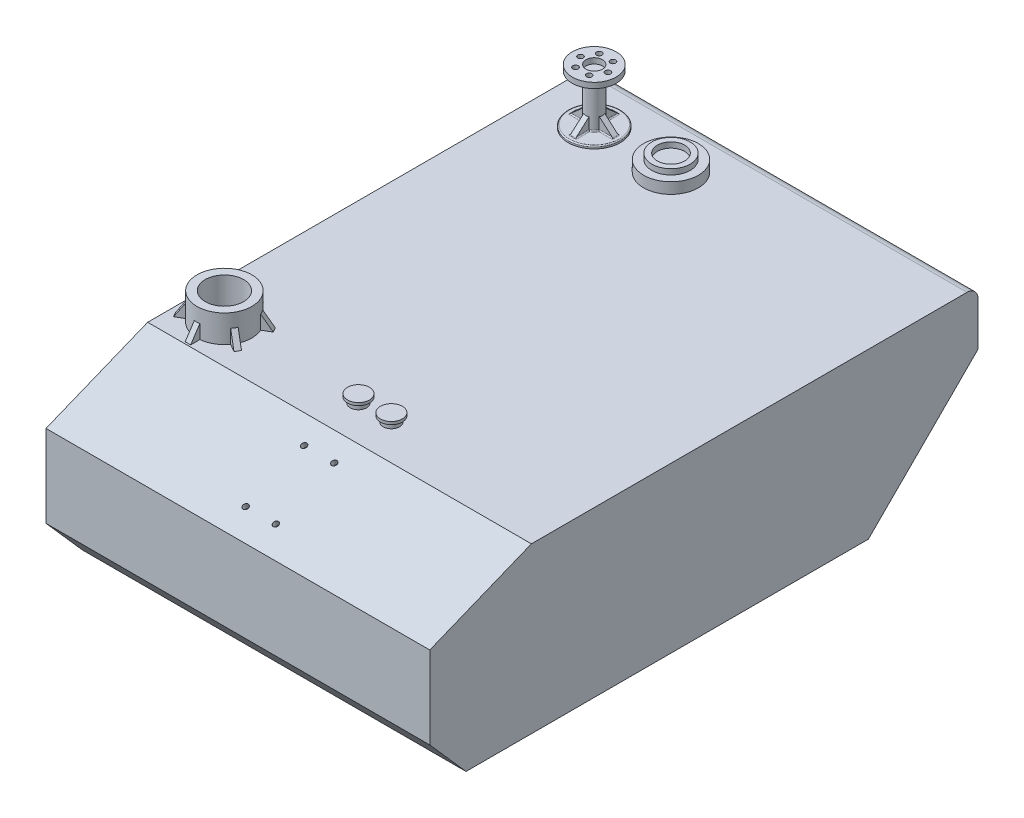
SolidWorks part; units mm, degrees
ref_plane "Front Plane" through (0, 0, 0) normal (0, 0, 1) x (1, 0, 0)
ref_plane "Top Plane" through (0, 0, 0) normal (0, 1, 0) x (1, 0, 0)
ref_plane "Right Plane" through (0, 0, 0) normal (1, 0, 0) x (0, 0, -1)
sketch "Sketch2" plane through (0, 0, 0) normal (0, 1, 0) x (1, 0, 0)
  line L1 (350, 500) -> (-350, 500)
  line L2 (350, 500) -> (350, -500)
  line L3 (350, -500) -> (-350, -500)
  line L4 (-350, 500) -> (-350, -500)
  line L5 (350, 500) -> (-350, -500) construction
  line L6 (350, -500) -> (-350, 500) construction
  point P0 (0, 0)
  dimension "D1" = 1000
  dimension "D2" = 700
extrude "Boss-Extrude1" add sketch "Sketch2" along normal blind 300
sketch "Sketch3" plane through (0, 300, 0) normal (0, 1, 0) x (1, 0, 0)
  line L0 (350, 500) -> (-350, 500) construction
  line L1 (-350, 500) -> (-350, -500) construction
  circle A0 centre (-250, 400) radius 15
  dimension "D4" = 30
  dimension "D1" = 90
  dimension "D2" = 100
  dimension "D3" = 100
extrude "Boss-Extrude2" add sketch "Sketch3" along normal blind 100
sketch "Sketch5" plane through (-350, 0, 0) normal (-1, 0, 0) x (0, 0, 1)
  line L0 (314.595, 300) -> (500, 300)
  line L1 (-500, 300) -> (500, 300) construction
  line L2 (500, 300) -> (500, 225)
  line L3 (500, 300) -> (500, 0) construction
  line L4 (500, 225) -> (314.595, 300)
  dimension "D1" = 200
  dimension "D2" = 75
extrude "Cut-Extrude2" cut sketch "Sketch5" against normal through all
sketch "Sketch6" plane through (-350, 0, 0) normal (-1, 0, 0) x (0, 0, 1)
  line L0 (433.8562, 0) -> (500, 75)
  line L1 (-500, 0) -> (500, 0) construction
  line L2 (500, 225) -> (500, 0) construction
  line L3 (500, 75) -> (500, 0)
  line L4 (500, 0) -> (433.8562, 0)
  dimension "D1" = 100
  dimension "D2" = 75
extrude "Cut-Extrude3" cut sketch "Sketch6" against normal through all
sketch "Sketch7" plane through (-350, 0, 0) normal (-1, 0, 0) x (0, 0, 1)
  line L0 (-500, 200) -> (-300, 0)
  line L1 (-500, 300) -> (-500, 0) construction
  line L2 (-500, 0) -> (433.8562, 0) construction
  line L3 (-500, 200) -> (-500, 0)
  line L4 (-500, 0) -> (-300, 0)
  dimension "D1" = 200
  dimension "D2" = 200
extrude "Cut-Extrude4" cut sketch "Sketch7" against normal through all
fillet "Fillet1" radius 20 1 edges at (0, 300, -500)
sketch "Sketch8" plane through (0, 400, 0) normal (0, 1, 0) x (1, 0, 0)
  circle A0 centre (-250, 400) radius 40
  dimension "D1" = 80
extrude "Boss-Extrude3" add sketch "Sketch8" against normal blind 10
sketch "Sketch10" plane through (0, 390, 0) normal (0, -1, 0) x (-1, 0, 0)
  circle A0 centre (250, 400) radius 15
  dimension "D1" = 30
extrude "Cut-Extrude5" cut sketch "Sketch10" against normal blind 20
sketch "Sketch11" plane through (0, 390, 0) normal (0, -1, 0) x (-1, 0, 0)
  circle A0 centre (250, 400) radius 25 construction
  circle A2 centre (225, 400) radius 5
  circle A3 centre (237.5, 421.6506) radius 5
  circle A4 centre (262.5, 421.6506) radius 5
  circle A5 centre (275, 400) radius 5
  circle A6 centre (262.5, 378.3494) radius 5
  circle A7 centre (237.5, 378.3494) radius 5
  point P18 (250, 400)
  dimension "D1" = 50
  dimension "D2" = 10
  dimension "D3" = 6
extrude "Cut-Extrude6" cut sketch "Sketch11" against normal blind 10
ref_plane "Plane1" through (-250, 0, 0) normal (1, 0, 0) x (0, 0, -1)
sketch "Sketch13" plane through (-250, 0, 0) normal (1, 0, 0) x (0, 0, -1)
  line L0 (385, 326.4575) -> (355, 300)
  line L4 (385, 390) -> (385, 300) construction
  line L5 (-314.595, 300) -> (480, 300) construction
  dimension "D1" = 40
  dimension "D2" = 30
rib "Rib6" sketch "Sketch13" sketch "Sketch13" thickness 10 extrusion direction parallel to sketch draft on no parameters "D1"=10
pattern_circular "CirPattern1" count 4 over 360 about axis through (-250, 0, -400) along (0, 1, 0) of "Rib6"
sketch "Sketch14" plane through (0, 300, 0) normal (0, 1, 0) x (1, 0, 0)
  circle A0 centre (-250, 400) radius 47.5
  dimension "D1" = 95
extrude "Boss-Extrude4" add sketch "Sketch14" along normal blind 5
fillet "Fillet2" radius 2 17 edges at (-250, 305, -352.5) (-245, 305, -426.7363) (-250, 305, -439.3305) (-255, 305, -426.7363) (-260.6066, 305, -410.6066) (-276.7363, 305, -405) (-289.3305, 305, -400) (-276.7363, 305, -395) (-260.6066, 305, -389.3934) (-255, 305, -373.2637) (-250, 305, -360.6695) (-245, 305, -373.2637) (-239.3934, 305, -389.3934) (-223.2637, 305, -395) (-210.6695, 305, -400) (-223.2637, 305, -405) (-239.3934, 305, -410.6066)
sketch "Sketch15" plane through (0, 300, 0) normal (0, 1, 0) x (1, 0, 0)
  circle A0 centre (-110, 400) radius 50
  dimension "D2" = 100
  dimension "D1" = 110
extrude "Boss-Extrude5" add sketch "Sketch15" along normal blind 20
sketch "Sketch16" plane through (0, 320, 0) normal (0, 1, 0) x (1, 0, 0)
  circle A0 centre (-110, 400) radius 35
  dimension "D1" = 70
extrude "Boss-Extrude6" add sketch "Sketch16" along normal blind 10
sketch "Sketch17" plane through (0, 330, 0) normal (0, 1, 0) x (1, 0, 0)
  circle A0 centre (-110, 400) radius 25
  dimension "D1" = 50
extrude "Cut-Extrude7" cut sketch "Sketch17" against normal blind 10
sketch "Sketch18" plane through (0, 300, 0) normal (0, 1, 0) x (1, 0, 0)
  line L0 (-350, 480) -> (-350, -314.595) construction
  line L1 (350, -314.595) -> (-350, -314.595) construction
  circle A0 centre (-280, -244.595) radius 50
  circle A1 centre (-280, -244.595) radius 35
  dimension "D1" = 100
  dimension "D4" = 70
  dimension "D2" = 70
  dimension "D3" = 70
extrude "Boss-Extrude7" add sketch "Sketch18" along normal blind 50
ref_plane "Plane2" through (-280, 0, 0) normal (1, 0, 0) x (0, 0, -1)
sketch "Sketch19" plane through (-280, 0, 0) normal (1, 0, 0) x (0, 0, -1)
  line L0 (-294.595, 325) -> (-311.1782, 300)
  line L1 (-294.595, 350) -> (-294.595, 300) construction
  line L2 (-314.595, 300) -> (480, 300) construction
  dimension "D1" = 30
rib "Rib7" sketch "Sketch19" sketch "Sketch19" thickness 10 extrusion direction parallel to sketch draft on no parameters "D1"=10
pattern_circular "CirPattern2" count 6 over 360 about axis through (-280, 0, 244.595) along (0, 1, 0) of "Rib7"
sketch "Sketch20" plane through (0, 300, 0) normal (0, 1, 0) x (1, 0, 0)
  line L0 (0, 0) -> (0, -346.9294) construction
  circle A0 centre (-30, -250) radius 15
  circle A1 centre (30, -250) radius 15
  dimension "D1" = 30
  dimension "D2" = 30
  dimension "D3" = 30
  dimension "25" = 30
  dimension "D4" = 250
  dimension "D5" = 250
extrude "Boss-Extrude8" add sketch "Sketch20" along normal mid plane 20
sketch "Sketch21" plane through (0, 310, 0) normal (0, 1, 0) x (1, 0, 0)
  circle A0 centre (-30, -250) radius 20
  circle A1 centre (30, -250) radius 20
  dimension "D1" = 40
  dimension "D2" = 40
extrude "Boss-Extrude9" add sketch "Sketch21" along normal blind 5
sketch "Sketch22" plane through (0, 367.1765, 148.5302) normal (0, 0.927, 0.375) x (1, 0, 0)
  line L0 (0, 0) -> (0, -476.6959) construction
  line L1 (350, -179.1374) -> (-350, -179.1374) construction
  circle A0 centre (-27.5, -219.1374) radius 5
  circle A1 centre (27.5, -219.1374) radius 5
  circle A2 centre (27.5, -334.1374) radius 5
  circle A3 centre (-27.5, -334.1374) radius 5
  point P8 (0, 0)
  point P12 (0, 0)
  point P13 (0, 0)
  point P14 (0, 0)
  dimension "D2" = 10
  dimension "D3" = 10
  dimension "D1" = 55
  dimension "D4" = 27.5
  dimension "D6" = 115
  dimension "D7" = 40
  dimension "D5" = 2
extrude "Cut-Extrude8" cut sketch "Sketch22" against normal blind 10
